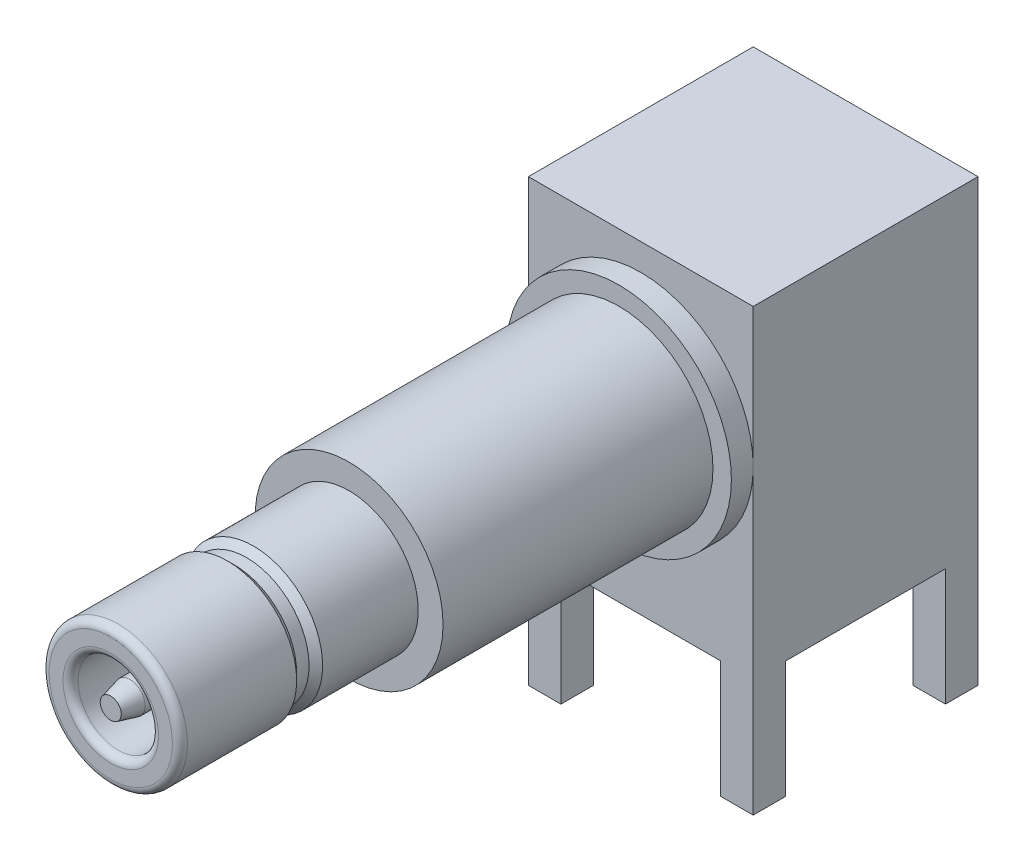
SolidWorks part; units mm, degrees
material "Laiton"
ref_plane "Front" through (0, 0, 0) normal (0, 0, 1) x (1, 0, 0)
ref_plane "Top" through (0, 0, 0) normal (0, 1, 0) x (1, 0, 0)
ref_plane "Right" through (0, 0, 0) normal (1, 0, 0) x (0, 0, -1)
sketch "Sketch1" plane through (0, 0, 0) normal (0, 1, 0) x (1, 0, 0)
  line L0 (0, 2.99) -> (0, -2.99) construction
  line L1 (-2.99, -2.99) -> (2.99, -2.99)
  line L2 (-2.99, -2.99) -> (-2.99, 2.99)
  line L3 (-2.99, 2.99) -> (2.99, 2.99)
  line L4 (2.99, -2.99) -> (2.99, 2.99)
  point P7 (0, 0)
  dimension "D1" = 5.98
  dimension "D2" = 5.98
extrude "Extrude1" add sketch "Sketch1" along normal blind 8.6
sketch "Sketch3" plane through (0, 0, 0) normal (0, -1, 0) x (1, 0, 0)
  line L0 (-2.125, 2.125) -> (2.125, 2.125) construction
  line L1 (2.125, 2.125) -> (2.125, -2.125) construction
  line L2 (2.125, -2.125) -> (-2.125, -2.125) construction
  line L3 (-2.125, -2.125) -> (-2.125, 2.125) construction
  line L4 (2.99, 2.99) -> (2.125, 2.99)
  line L5 (2.99, 2.99) -> (2.99, 2.125)
  line L6 (2.99, 2.125) -> (2.125, 2.125)
  line L7 (2.125, 2.99) -> (2.125, 2.125)
  line L8 (0, 2.125) -> (0, 2.99) construction
  line L9 (2.99, -2.99) -> (2.125, -2.99)
  line L10 (2.125, -2.99) -> (2.125, -2.125)
  line L11 (2.99, -2.125) -> (2.125, -2.125)
  line L12 (2.99, -2.99) -> (2.99, -2.125)
  line L13 (-2.99, -2.99) -> (-2.99, -2.125)
  line L14 (-2.99, -2.125) -> (-2.125, -2.125)
  line L15 (-2.125, -2.99) -> (-2.125, -2.125)
  line L16 (-2.99, -2.99) -> (-2.125, -2.99)
  line L17 (-2.99, 2.99) -> (-2.99, 2.125)
  line L18 (-2.99, 2.99) -> (-2.125, 2.99)
  line L19 (-2.125, 2.99) -> (-2.125, 2.125)
  line L20 (-2.99, 2.125) -> (-2.125, 2.125)
  line L21 (-2.99, 2.99) -> (2.99, 2.99) construction
  line L22 (2.125, 0) -> (2.99, 0) construction
  line L23 (2.99, 2.99) -> (2.99, -2.99) construction
  dimension "D1" = 4.25
  dimension "D2" = 4.25
extrude "Extrude3" add sketch "Sketch3" along normal blind 3.12
sketch "Sketch4" plane through (0, 0, 0) normal (0, -1, 0) x (1, 0, 0)
  line L0 (0, 2.99) -> (0, -2.99) construction
  line L1 (-2.125, 2.99) -> (2.125, 2.99) construction
  line L2 (2.125, -2.99) -> (-2.125, -2.99) construction
  line L3 (2.99, 0) -> (-2.99, 0) construction
  line L4 (2.99, 2.125) -> (2.99, -2.125) construction
  line L5 (-2.99, -2.125) -> (-2.99, 2.125) construction
  circle A0 centre (0, 0) radius 1.6936
extrude "Cut-Extrude1" cut sketch "Sketch4" against normal blind 0.254
sketch "Sketch5" plane through (0, 0.254, 0) normal (0, -1, 0) x (1, 0, 0)
  circle A0 centre (0, 0) radius 0.4826
  dimension "D1" = 0.9652
extrude "Extrude4" add sketch "Sketch5" along normal up to surface (3.374 mm away) up to face at (2.5575, -3.12, 2.5575)
sketch "Sketch6" plane through (0, 0, 2.99) normal (0, 0, 1) x (1, 0, 0)
  line L5 (0, 8.6) -> (0, 0) construction
  line L6 (-2.99, 8.6) -> (2.99, 8.6) construction
  line L7 (-2.125, 0) -> (2.125, 0) construction
  circle A0 centre (0, 4.9) radius 2.99
  dimension "D2" = 4.9
  dimension "D1" = 5.98
extrude "Extrude5" add sketch "Sketch6" along normal blind 0.58
sketch "Esquisse1" plane through (0, 0, 3.57) normal (0, 0, 1) x (1, 0, 0)
  circle A0 centre (0, 4.9) radius 2.5
  dimension "D1" = 5
extrude "Boss.-Extru.1" add sketch "Esquisse1" along normal blind 7.18
sketch "Sketch7" plane through (0, 0, 10.75) normal (0, 0, 1) x (1, 0, 0)
  circle A0 centre (0, 4.9) radius 1.84
  dimension "D1" = 3.68
extrude "Extrude6" add sketch "Sketch7" along normal blind 6.34
ref_axis "Axis1" through (0, 4.9, 17.09) along (0, 0, -1)
ref_plane "Plane1" through (0, 4.9, 0) normal (0, 1, 0) x (-1, 0, 0)
sketch "Sketch9" plane through (0, 0, 17.09) normal (0, 0, 1) x (1, 0, 0)
  circle A0 centre (0, 4.9) radius 1.07
  dimension "D1" = 2.14
sketch "Esquisse2" plane through (0, 4.9, 0) normal (0, 1, 0) x (-1, 0, 0)
  line L0 (0, 17.09) -> (0, 10.75) construction
  line L1 (-2.3671, 14.5121) -> (-1.66, 13.805)
  line L2 (-2.3671, 14.5121) -> (-2.3671, 12.7679)
  line L3 (-2.3671, 12.7679) -> (-1.66, 13.475)
  line L4 (-1.66, 13.805) -> (-1.66, 13.475)
  line L5 (1.84, 17.09) -> (-1.84, 17.09) construction
  line L6 (2.5, 10.75) -> (-2.5, 10.75) construction
  dimension "D1" = 0.33
  dimension "D2" = 3.32
  dimension "D3" = 1
  dimension "D4" = 135
  dimension "D5" = 135
  dimension "D6" = 3.285
revolve "Enlèvement de matière-Révolution1" cut sketch "Esquisse2" angle 360 about axis through (0, 4.9, 17.09) along (0, 0, -1)
extrude "Cut-Extrude2" cut sketch "Sketch9" against normal blind 5.6581
sketch "Sketch10" plane through (0, 0, 11.4319) normal (0, 0, 1) x (1, 0, 0)
  circle A0 centre (0, 4.9) radius 0.407
extrude "Extrude7" add sketch "Sketch10" along normal blind 5.6581
chamfer "Chamfer1" distance 0.508 angle 14 1 edges at (0.407, 4.9, 17.09)
fillet "Congé1" radius 0.2 2 edges at (1.84, 4.9, 17.09) (1.07, 4.9, 17.09)
chamfer "Chanfrein1" [suppressed] distance 0.4 angle 45
